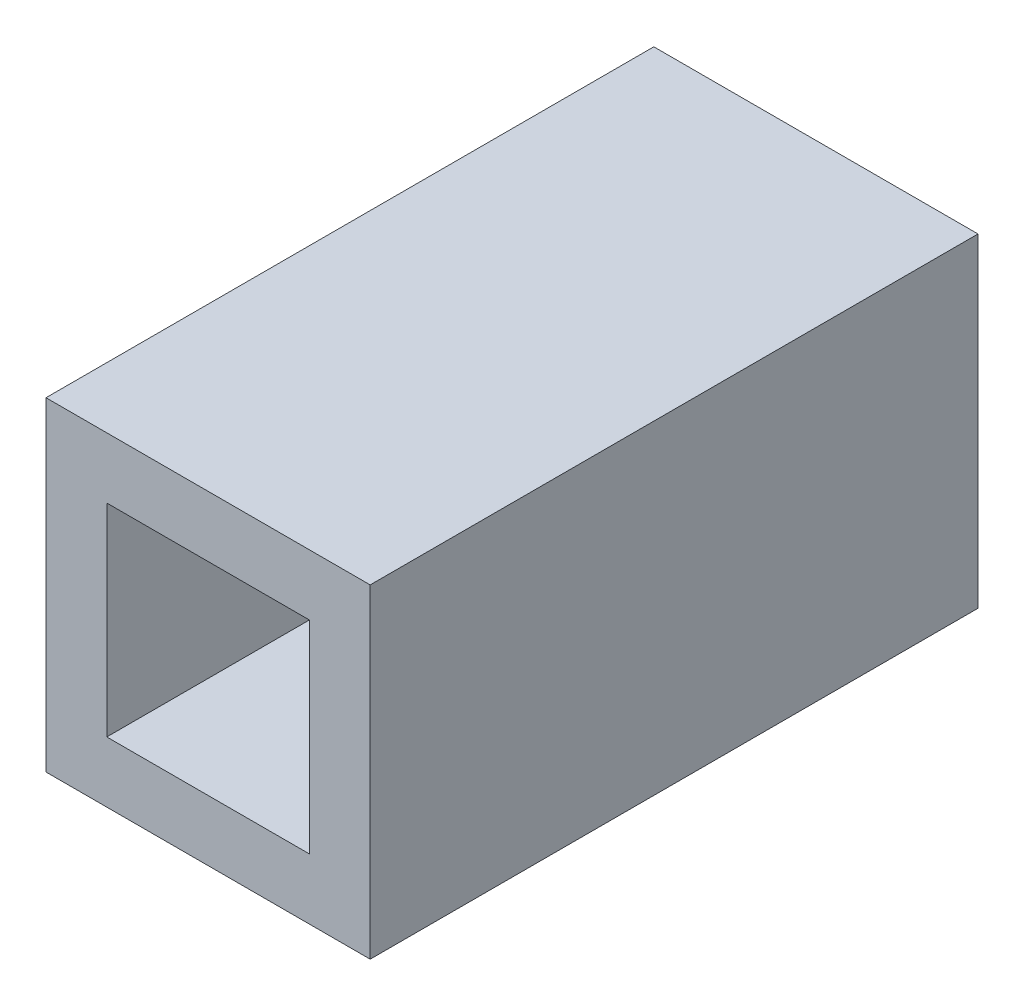
SolidWorks part; units mm, degrees
ref_plane "Front Plane" through (0, 0, 0) normal (0, 0, 1) x (1, 0, 0)
ref_plane "Top Plane" through (0, 0, 0) normal (0, 1, 0) x (1, 0, 0)
ref_plane "Right Plane" through (0, 0, 0) normal (1, 0, 0) x (0, 0, -1)
sketch "Sketch1" plane through (0, 0, 0) normal (0, 0, 1) x (1, 0, 0)
  line L0 (25, 25) -> (-25, 25)
  line L1 (40, 40) -> (-40, 40)
  line L2 (40, 40) -> (40, -40)
  line L3 (40, -40) -> (-40, -40)
  line L4 (-40, 40) -> (-40, -40)
  line L5 (40, 40) -> (-40, -40) construction
  line L6 (40, -40) -> (-40, 40) construction
  line L7 (-25, 25) -> (-25, -25)
  line L8 (25, -25) -> (-25, -25)
  line L9 (25, 25) -> (25, -25)
  point P0 (0, 0)
  dimension "D1" = 80
  dimension "D2" = 15
extrude "Boss-Extrude1" add sketch "Sketch1" along normal blind 150
sketch "Sketch2" plane through (-40, 0, 0) normal (-1, 0, 0) x (0, 0, 1)
  line L0 (150, 40) -> (0, 40) construction
  line L1 (0, 40) -> (0, -40) construction
  circle A0 centre (75, 0) radius 5
  point P5 (75, 40)
  point P8 (0, 0)
  dimension "D1" = 10
extrude "Cut-Extrude1" cut sketch "Sketch2" against normal blind 5
ref_plane "Plane1" through (-115, 0, 0) normal (-1, 0, 0) x (0, 0, 1)
ref_plane "Plane2" through (0, 0, 0) normal (-1, 0, 0) x (0, 0, 1)
sketch "Sketch5" plane through (0, 0, 0) normal (-1, 0, 0) x (0, 0, 1)
  line L0 (-25, 0) -> (75, 0) construction
  line L1 (75, 0) -> (75, -100) construction
  circle A0 centre (75, 0) radius 5 construction
  text T0 "Z2" font "Century Gothic" height 20
  text T1 "X2" font "Century Gothic" height 20
sketch "Sketch6" plane through (0, 0, 0) normal (0, 1, 0) x (1, 0, 0)
  line L0 (0, -75) -> (-100, -75) construction
  line L1 (0, 25) -> (0, -75) construction
  text T0 "Y2" font "Century Gothic" height 20
